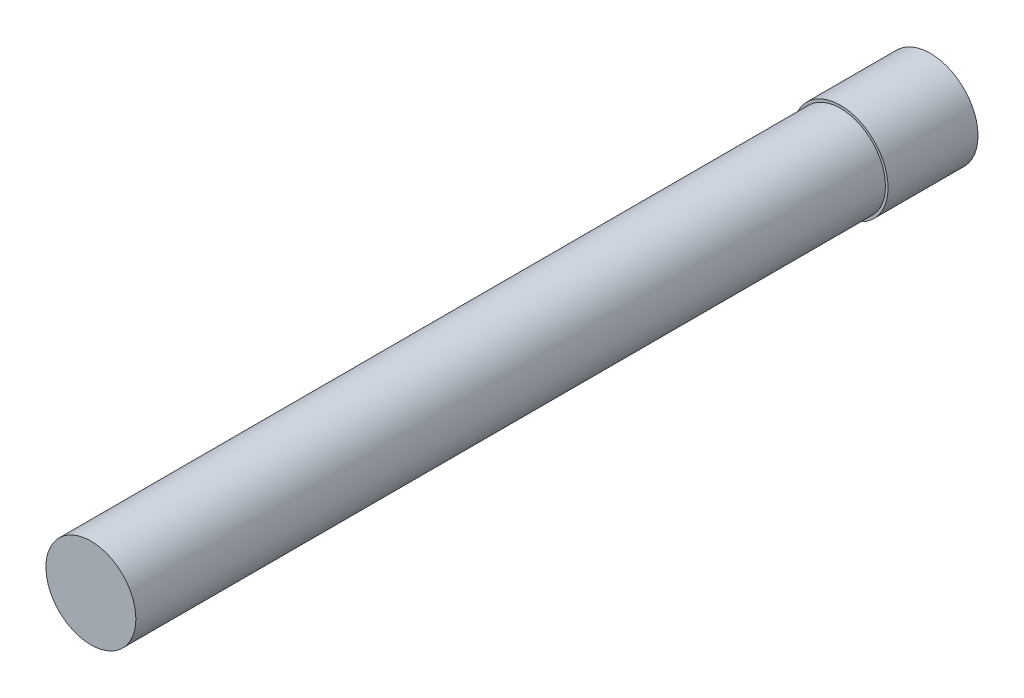
SolidWorks part; units mm, degrees
ref_plane "Front Plane" through (0, 0, 0) normal (1, 0, 0) x (0, 1, 0)
ref_plane "Top Plane" through (0, 0, 0) normal (0, 0, 1) x (0, 1, 0)
ref_plane "Right Plane" through (0, 0, 0) normal (0, 1, 0) x (-1, 0, 0)
sketch "Sketch1" plane through (0, 0, 0) normal (0, 0, 1) x (0, 1, 0)
  circle A0 centre (0, 0) radius 3.175
  dimension "D1" = 6.35
extrude "Boss-Extrude1" add sketch "Sketch1" along normal blind 6
sketch "Sketch2" plane through (0, 0, 6) normal (0, 0, 1) x (1, 0, 0)
  circle A0 centre (0, 0) radius 3
  dimension "D1" = 6
extrude "Boss-Extrude2" add sketch "Sketch2" along normal blind 50
